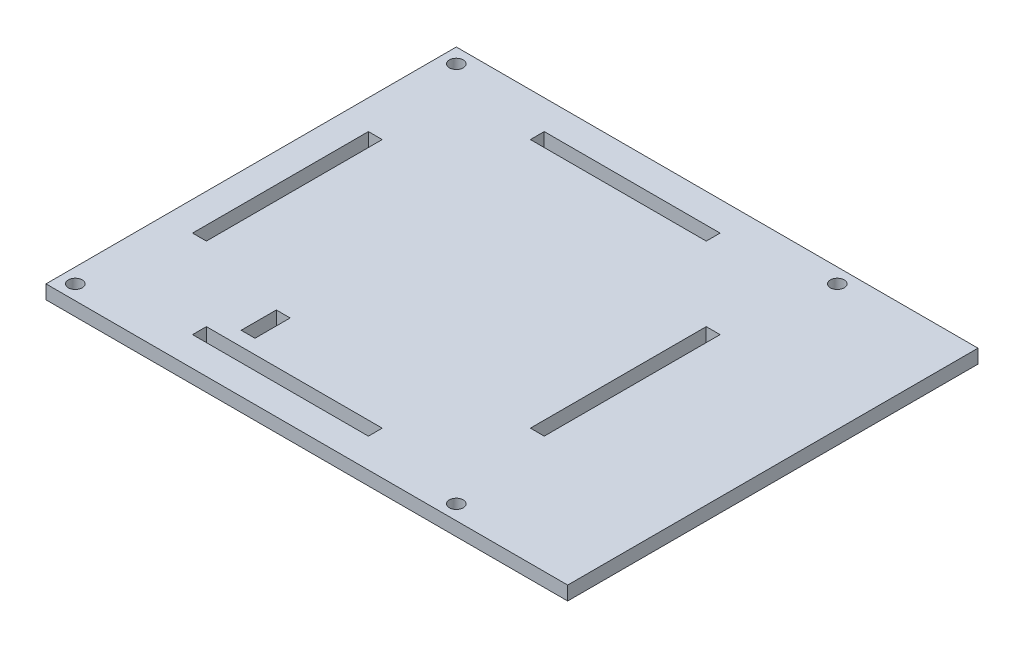
SolidWorks part; units mm, degrees
material "Acrylic (Medium-high impact)"
ref_plane "Front Plane" through (0, 0, 0) normal (0, 0, 1) x (1, 0, 0)
ref_plane "Top Plane" through (0, 0, 0) normal (0, 1, 0) x (1, 0, 0)
ref_plane "Right Plane" through (0, 0, 0) normal (1, 0, 0) x (0, 0, -1)
sketch "스케치4" plane through (0, 0, 0) normal (0, 1, 0) x (1, 0, 0)
  line L0 (-38.1, 38.1) -> (-44.45, 44.45) construction
  line L1 (-44.45, -44.45) -> (44.45, -44.45)
  line L2 (-44.45, -44.45) -> (-44.45, 44.45)
  line L3 (-44.45, 44.45) -> (44.45, 44.45)
  line L4 (44.45, -44.45) -> (44.45, 44.45)
  line L5 (-44.45, -44.45) -> (44.45, 44.45) construction
  line L6 (-44.45, 44.45) -> (44.45, -44.45) construction
  line L7 (-38.1, -38.1) -> (38.1, -38.1) construction
  line L8 (-38.1, -38.1) -> (-38.1, 38.1) construction
  line L9 (-38.1, 38.1) -> (38.1, 38.1) construction
  line L10 (38.1, -38.1) -> (38.1, 38.1) construction
  line L11 (-38.1, -38.1) -> (38.1, 38.1) construction
  line L12 (-38.1, 38.1) -> (38.1, -38.1) construction
  line L13 (38.1, -38.1) -> (44.45, -44.45) construction
  line L14 (0, 36.6) -> (0, 0) construction
  line L15 (-19.05, 35.1) -> (19.05, 35.1)
  line L16 (-19.05, 35.1) -> (-19.05, 38.1)
  line L17 (-19.05, 38.1) -> (19.05, 38.1)
  line L18 (19.05, 35.1) -> (19.05, 38.1)
  line L19 (-19.05, 35.1) -> (19.05, 38.1) construction
  line L20 (-19.05, 38.1) -> (19.05, 35.1) construction
  line L21 (35.1, 19.05) -> (38.1, 19.05)
  line L22 (35.1, 19.05) -> (35.1, -19.05)
  line L23 (35.1, -19.05) -> (38.1, -19.05)
  line L24 (38.1, 19.05) -> (38.1, -19.05)
  line L25 (19.05, -35.1) -> (19.05, -38.1)
  line L26 (19.05, -35.1) -> (-19.05, -35.1)
  line L27 (-19.05, -35.1) -> (-19.05, -38.1)
  line L28 (19.05, -38.1) -> (-19.05, -38.1)
  line L29 (-35.1, -19.05) -> (-38.1, -19.05)
  line L30 (-35.1, -19.05) -> (-35.1, 19.05)
  line L31 (-35.1, 19.05) -> (-38.1, 19.05)
  line L32 (-38.1, -19.05) -> (-38.1, 19.05)
  line L33 (0, -35.1) -> (0, 0) construction
  circle A0 centre (-41.275, 41.275) radius 2.8575 construction
  circle A1 centre (-41.275, 41.275) radius 1.5
  circle A2 centre (41.275, 41.275) radius 1.5
  circle A3 centre (41.275, -41.275) radius 1.5
  circle A4 centre (-41.275, -41.275) radius 1.5
  point P0 (0, 0)
  point P6 (0, 0)
  point P11 (0, 36.6)
  point P23 (0, 0)
  point P43 (0, 0)
  dimension "D4" = 5.715
  dimension "D5" = 3
  dimension "D7" = 3
  dimension "D1" = 88.9
  dimension "D2" = 88.9
  dimension "D3" = 76.2
  dimension "D8" = 38.1
  dimension "D6" = 4
  dimension "D9" = 4
extrude "보스-돌출1" add sketch "스케치4" along normal blind 3
sketch "스케치6" plane through (44.45, 0, 0) normal (1, 0, 0) x (0, 0, -1)
  line L4 (-44.45, 0) -> (44.45, 0)
  line L5 (44.45, 0) -> (44.45, 3)
  line L6 (44.45, 3) -> (-44.45, 3)
  line L7 (-44.45, 3) -> (-44.45, 0)
  line L8 (-44.45, 0) -> (44.45, 0)
  line L9 (44.45, 0) -> (44.45, 3)
  line L10 (44.45, 3) -> (-44.45, 3)
  line L11 (-44.45, 3) -> (-44.45, 0)
  dimension "D1" = 0
extrude "보스-돌출2" add sketch "스케치6" along normal blind 24.13
sketch "스케치7" plane through (0, 3, 0) normal (0, 1, 0) x (1, 0, 0)
  line L0 (-35.1, -19.05) -> (-35.1, 19.05) construction
  line L1 (-14.6, -24.4002) -> (-11.6, -24.4002)
  line L2 (-14.6, -24.4002) -> (-14.6, -32.0202)
  line L3 (-14.6, -32.0202) -> (-11.6, -32.0202)
  line L4 (-11.6, -24.4002) -> (-11.6, -32.0202)
  line L5 (-14.6, -24.4002) -> (-11.6, -32.0202) construction
  line L6 (-14.6, -32.0202) -> (-11.6, -24.4002) construction
  line L7 (-14.6, -35.1) -> (-14.6, -21.3205) construction
  line L8 (19.05, -35.1) -> (-19.05, -35.1) construction
  line L9 (-13.1, -28.2102) -> (-14.6, -28.2102) construction
  point P0 (-13.1, -28.2102)
  dimension "D1" = 7.62
  dimension "D2" = 20.5
  dimension "D3" = 3
  dimension "D4" = 13.7795
extrude "컷-돌출1" cut sketch "스케치7" against normal up to surface (3 mm away) up to face at (41.275, 0, 42.775)
